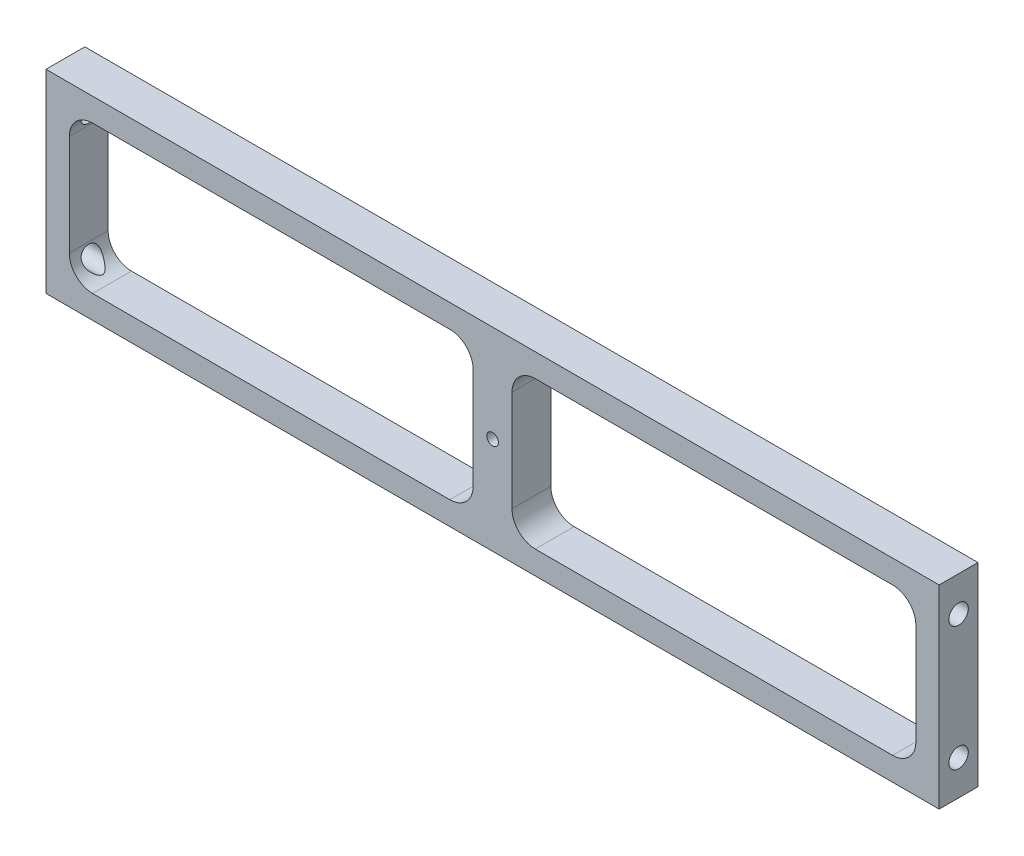
SolidWorks part; units mm, degrees
ref_plane "前视基准面" through (0, 0, 0) normal (0, 0, 1) x (1, 0, 0)
ref_plane "上视基准面" through (0, 0, 0) normal (0, 1, 0) x (1, 0, 0)
ref_plane "右视基准面" through (0, 0, 0) normal (1, 0, 0) x (0, 0, -1)
sketch "草图1" plane through (0, 0, 0) normal (0, 0, 1) x (1, 0, 0)
  line L0 (6, 44) -> (224, 44)
  line L1 (0, 0) -> (230, 0)
  line L2 (0, 0) -> (0, 50)
  line L3 (0, 50) -> (230, 50)
  line L4 (230, 0) -> (230, 50)
  line L5 (224, 6) -> (224, 44)
  line L6 (6, 6) -> (224, 6)
  line L7 (6, 6) -> (6, 44)
  line L8 (115, 50) -> (115, 0) construction
  line L9 (110, 44) -> (110, 6)
  line L10 (120, 44) -> (120, 6)
  dimension "D1" = 50
  dimension "D2" = 230
  dimension "D4" = 5
  dimension "D3" = 6
extrude "凸台-拉伸1" add sketch "草图1" along normal blind 10 contours L8 L3 L2 L1 L6 L7 L0 | L0 L8 L6 L10 | L8 L0 L9 L6 | L3 L8 L0 L5 L6 L1 L4
fillet "圆角1" radius 6 8 edges at (224, 44, 5) (224, 6, 5) (120, 44, 5) (120, 6, 5) (110, 6, 5) (110, 44, 5) (6, 6, 5) (6, 44, 5)
sketch "草图8" plane through (0, 0, 0) normal (-1, 0, 0) x (0, 0, 1)
  circle A2 centre (5, 41) radius 2.5
  circle A3 centre (5, 9) radius 2.5
extrude "切除-拉伸4" cut sketch "草图8" against normal blind 91
sketch "草图10" plane through (230, 0, 0) normal (1, 0, 0) x (0, 0, -1)
  circle A0 centre (-5, 41) radius 2.5
  circle A1 centre (-5, 9) radius 2.5
extrude "切除-拉伸5" cut sketch "草图10" against normal blind 91
sketch "草图2" plane through (0, 0, 0) normal (-1, 0, 0) x (0, 0, 1)
  line L0 (5, 50) -> (5, 0) construction
  line L1 (10, 50) -> (0, 50) construction
  line L2 (0, 25) -> (10, 25) construction
  line L3 (0, 0) -> (0, 50) construction
  line L4 (10, 0) -> (10, 50) construction
  circle A0 centre (5, 44) radius 2.5
  circle A1 centre (5, 6) radius 2.5
  dimension "D1" = 6
extrude "切除-拉伸1" [suppressed] cut sketch "草图2" against normal through all
sketch "草图11" plane through (230, 0, 0) normal (1, 0, 0) x (0, 0, -1)
  circle A1 centre (-5, 6) radius 2.5
  circle A2 centre (-5, 44) radius 2.5
extrude "凸台-拉伸2" [suppressed] add sketch "草图11" against normal blind 230
sketch "草图12" [suppressed] plane through (0, 0, 0) normal (0, 0, -1) x (-1, 0, 0)
  line L0 (-218, 44) -> (-126, 44)
  line L2 (-120, 38) -> (-120, 12)
  line L4 (-126, 6) -> (-218, 6)
  line L6 (-224, 12) -> (-224, 38)
  line L9 (-6, 12) -> (-6, 38)
  line L10 (-106, 6) -> (-12, 6)
  line L11 (-112, 38) -> (-112, 12)
  line L12 (-12, 44) -> (-106, 44)
  arc A0 (-218, 44) -> (-224, 38) centre (-218, 38) ccw
  arc A1 (-224, 12) -> (-218, 6) centre (-218, 12) ccw
  arc A2 (-120, 38) -> (-126, 44) centre (-126, 38) ccw
  arc A3 (-126, 6) -> (-120, 12) centre (-126, 12) ccw
  arc A4 (-106, 6) -> (-112, 12) centre (-106, 12) cw
  arc A5 (-112, 38) -> (-106, 44) centre (-106, 38) cw
  arc A6 (-6, 12) -> (-12, 6) centre (-12, 12) cw
  arc A7 (-12, 44) -> (-6, 38) centre (-12, 38) cw
extrude "切除-拉伸6" [suppressed] cut sketch "草图12" against normal blind 230
sketch "草图13" [suppressed] plane through (230, 0, 0) normal (1, 0, 0) x (0, 0, -1)
  circle A0 centre (-5, 41) radius 2.5
  circle A1 centre (-5, 9) radius 2.5
extrude "切除-拉伸7" [suppressed] cut sketch "草图13" against normal blind 75
sketch "草图14" plane through (0, 0, 0) normal (-1, 0, 0) x (0, 0, 1)
  circle A0 centre (5, 41) radius 2.5
  circle A1 centre (5, 9) radius 2.5
extrude "切除-拉伸8" [suppressed] cut sketch "草图14" against normal blind 75
sketch "草图15" plane through (0, 0, 10) normal (0, 0, 1) x (1, 0, 0)
  circle A0 centre (115, 25) radius 1.5
extrude "切除-拉伸9" cut sketch "草图15" against normal blind 10
